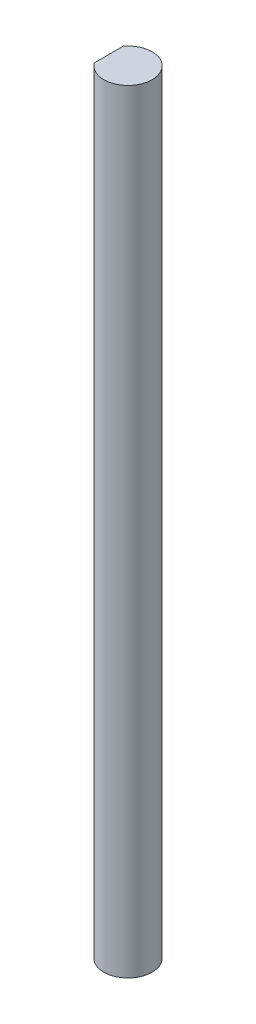
SolidWorks part; units mm, degrees
ref_plane "Front Plane" through (0, 0, 0) normal (0, 0, 1) x (1, 0, 0)
ref_plane "Top Plane" through (0, 0, 0) normal (0, 1, 0) x (1, 0, 0)
ref_plane "Right Plane" through (0, 0, 0) normal (1, 0, 0) x (0, 0, -1)
sketch "Sketch1" plane through (0, 0, 0) normal (0, 1, 0) x (1, 0, 0)
  line L0 (-2.54, -1.905) -> (-2.54, 1.905)
  line L1 (0, -3.175) -> (0, 3.175) construction
  line L2 (-2.54, 0) -> (3.175, 0) construction
  arc A0 (-2.54, -1.905) -> (-2.54, 1.905) centre (0, 0) ccw
  dimension "D1" = 6.35
  dimension "D2" = 5.715
extrude "Boss-Extrude1" add sketch "Sketch1" along normal blind 101.6
